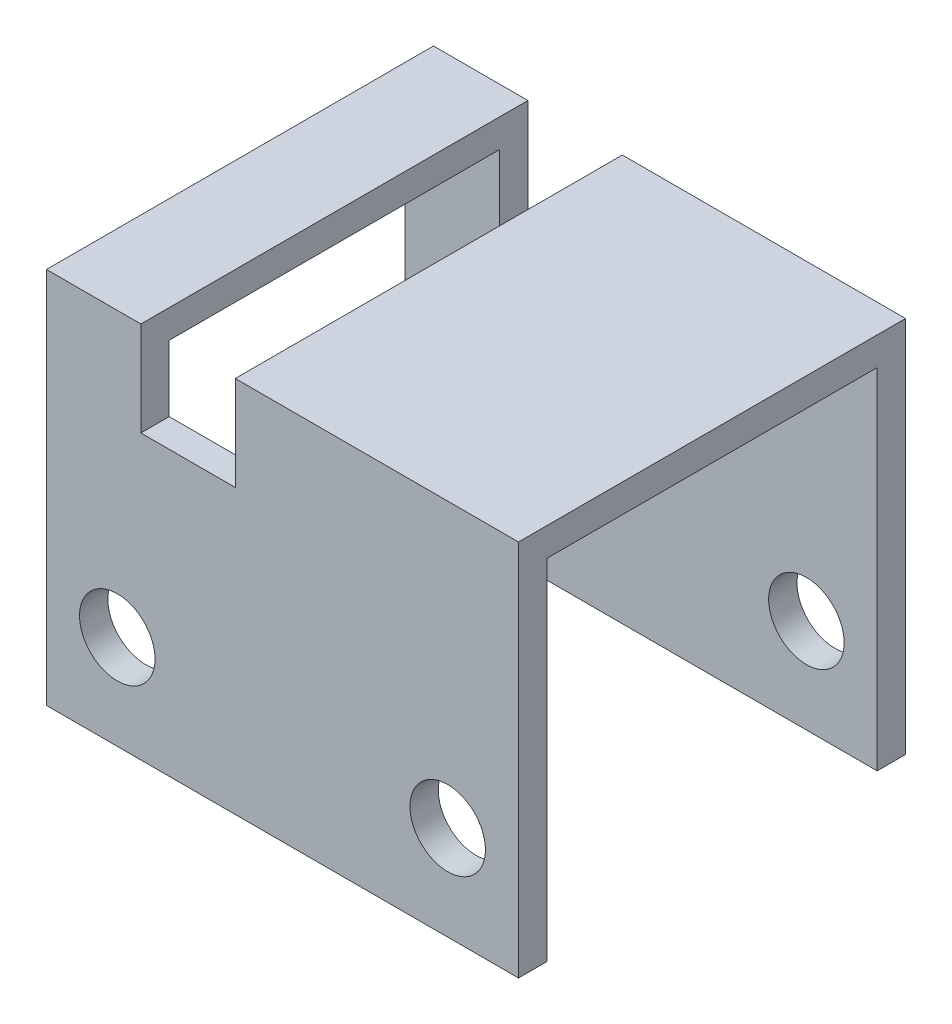
SolidWorks part; units mm, degrees
ref_plane "正面" through (0, 0, 0) normal (0, 0, 1) x (1, 0, 0)
ref_plane "平面" through (0, 0, 0) normal (0, 1, 0) x (1, 0, 0)
ref_plane "右側面" through (0, 0, 0) normal (1, 0, 0) x (0, 0, -1)
sketch "ｽｹｯﾁ1" plane through (0, 0, 0) normal (0, 0, 1) x (1, 0, 0)
  line L0 (-25, -37) -> (25, -37)
  line L2 (-25, -37) -> (-25, 3)
  line L4 (25, -37) -> (25, 3)
  line L5 (-25, 3) -> (-15, 3)
  line L6 (-15, 3) -> (-15, -7)
  line L7 (-15, -7) -> (-5, -7)
  line L8 (-5, -7) -> (-5, 3)
  line L9 (-5, 3) -> (25, 3)
  point P4 (0, -37)
  dimension "D1" = 50
  dimension "D2" = 40
  dimension "D3" = 3
  dimension "D4" = 10
  dimension "D5" = 10
  dimension "D6" = 10
extrude "ﾎﾞｽ - 押し出し1" add sketch "ｽｹｯﾁ1" along normal blind 41
sketch "ｽｹｯﾁ2" plane through (25, 0, 0) normal (1, 0, 0) x (0, 0, -1)
  line L0 (-41, -37) -> (0, -37) construction
  line L1 (-38, -37) -> (-3, -37)
  line L2 (-38, -37) -> (-38, 0)
  line L3 (-38, 0) -> (-3, 0)
  line L4 (-3, -37) -> (-3, 0)
  line L5 (-41, -37) -> (-41, 3) construction
  line L6 (0, -37) -> (0, 3) construction
  line L7 (-41, 3) -> (0, 3) construction
  dimension "D1" = 3
  dimension "D2" = 3
  dimension "D3" = 3
extrude "ｶｯﾄ - 押し出し1" cut sketch "ｽｹｯﾁ2" against normal through all
sketch "ｽｹｯﾁ3" plane through (0, 0, 41) normal (0, 0, 1) x (1, 0, 0)
  line L0 (-17.5, -27) -> (17.5, -27) construction
  line L2 (-25, -37) -> (25, -37) construction
  circle A0 centre (-17.5, -27) radius 4
  circle A1 centre (17.5, -27) radius 4
  point P4 (0, -27)
  dimension "D1" = 8
  dimension "D2" = 35
  dimension "D3" = 10
extrude "ｶｯﾄ - 押し出し2" cut sketch "ｽｹｯﾁ3" against normal through all
